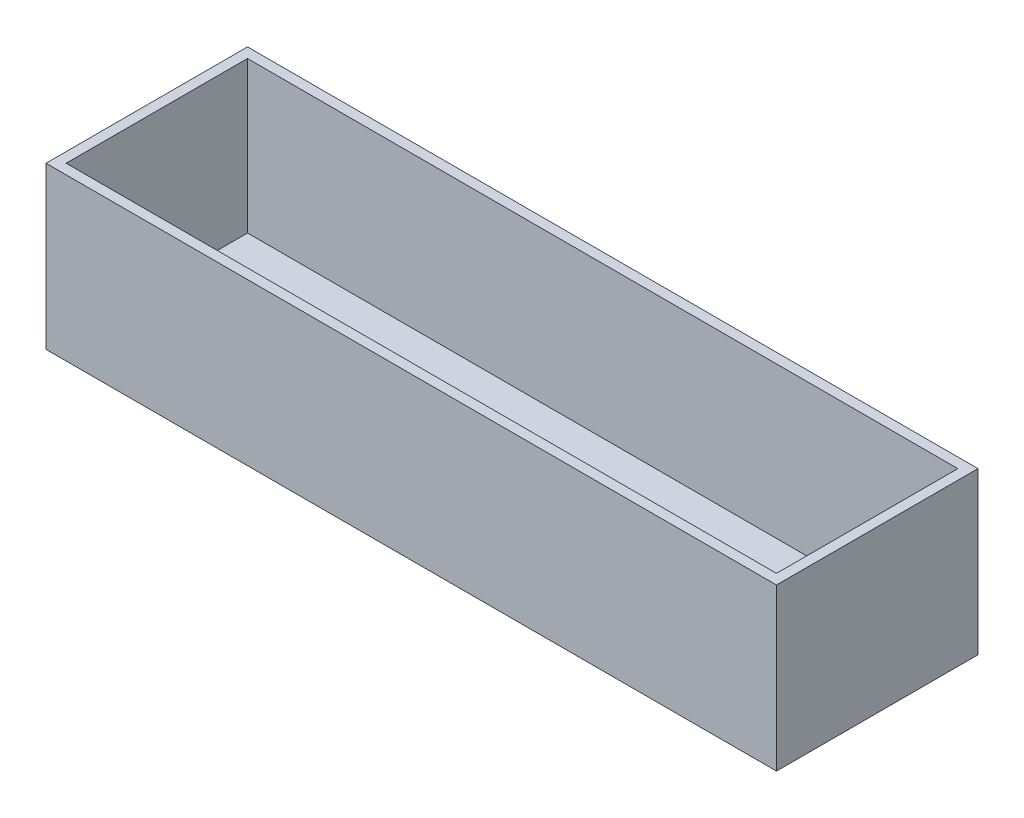
SolidWorks part; units mm, degrees
ref_plane "Front Plane" through (0, 0, 0) normal (0, 0, 1) x (1, 0, 0)
ref_plane "Top Plane" through (0, 0, 0) normal (0, 1, 0) x (1, 0, 0)
ref_plane "Right Plane" through (0, 0, 0) normal (1, 0, 0) x (0, 0, -1)
sketch "Sketch1" plane through (0, 0, 0) normal (0, 1, 0) x (1, 0, 0)
  line L0 (0, 0) -> (-72.5, 0) construction
  line L1 (-72.5, 20) -> (72.5, 20)
  line L2 (-72.5, 20) -> (-72.5, -20)
  line L3 (-72.5, -20) -> (72.5, -20)
  line L4 (72.5, 20) -> (72.5, -20)
  line L5 (0, 0) -> (0, 20) construction
  line L6 (-70.5, 18) -> (-70.5, -18)
  line L7 (-70.5, -18) -> (70.5, -18)
  line L8 (70.5, 18) -> (70.5, -18)
  line L9 (-70.5, 18) -> (70.5, 18)
  dimension "D1" = 145
  dimension "D2" = 40
  dimension "D3" = 2
extrude "Boss-Extrude1" add sketch "Sketch1" along normal blind 30
sketch "Sketch2" plane through (0, 0, 0) normal (0, -1, 0) x (1, 0, 0)
  line L4 (-72.5, 20) -> (-72.5, -20)
  line L5 (-72.5, -20) -> (72.5, -20)
  line L6 (72.5, -20) -> (72.5, 20)
  line L7 (72.5, 20) -> (-72.5, 20)
  line L8 (-72.5, 20) -> (-72.5, -20)
  line L9 (-72.5, -20) -> (72.5, -20)
  line L10 (72.5, -20) -> (72.5, 20)
  line L11 (72.5, 20) -> (-72.5, 20)
  dimension "D1" = 0
extrude "Boss-Extrude2" add sketch "Sketch2" along normal blind 2
